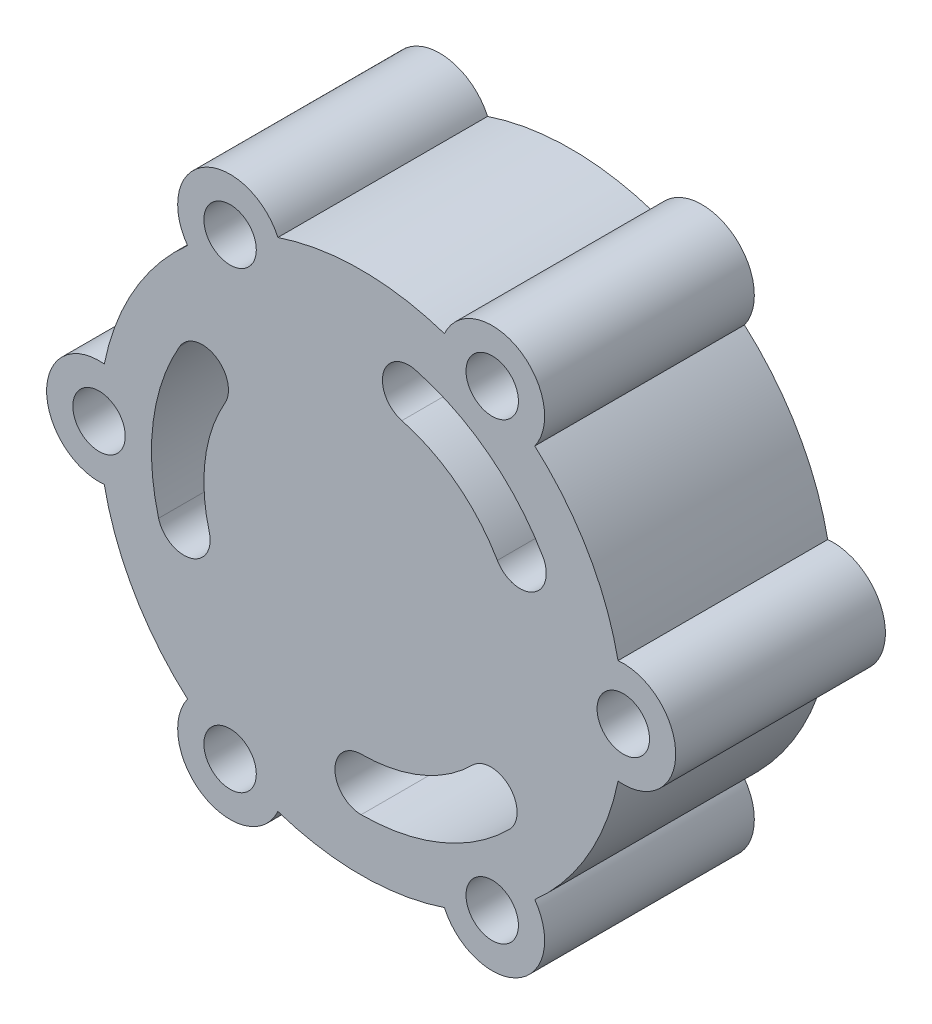
SolidWorks part; units mm, degrees
ref_plane "Front Plane" through (0, 0, 0) normal (0, 0, 1) x (1, 0, 0)
ref_plane "Top Plane" through (0, 0, 0) normal (0, 1, 0) x (1, 0, 0)
ref_plane "Right Plane" through (0, 0, 0) normal (1, 0, 0) x (0, 0, -1)
sketch "Sketch1" plane through (0, 0, 0) normal (0, 0, 1) x (1, 0, 0)
  line L0 (0, 0) -> (0, 50000) construction
  line L1 (0, 0) -> (-50000, 0) construction
  line L2 (70, 70) -> (105, 70) construction
  circle A0 centre (70, 70) radius 35 construction
  arc A1 (100.3109, 87.5) -> (79.0587, 103.8074) centre (70, 70) ccw construction
  arc A2 (104.641, 90) -> (80.3528, 108.637) centre (70, 70) ccw
  arc A3 (95.9808, 85) -> (77.7646, 98.9778) centre (70, 70) ccw
  arc A4 (95.9808, 85) -> (104.641, 90) centre (100.3109, 87.5) ccw
  arc A5 (80.3528, 108.637) -> (77.7646, 98.9778) centre (79.0587, 103.8074) ccw
  arc A6 (70, 35) -> (94.7487, 45.2513) centre (70, 70) ccw construction
  arc A7 (70, 30) -> (98.2843, 41.7157) centre (70, 70) ccw
  arc A8 (70, 40) -> (91.2132, 48.7868) centre (70, 70) ccw
  arc A9 (70, 40) -> (70, 30) centre (70, 35) ccw
  arc A10 (98.2843, 41.7157) -> (91.2132, 48.7868) centre (94.7487, 45.2513) ccw
  arc A11 (39.6891, 87.5) -> (36.1926, 60.9413) centre (70, 70) ccw construction
  arc A12 (35.359, 90) -> (31.363, 59.6472) centre (70, 70) ccw
  arc A13 (44.0192, 85) -> (41.0222, 62.2354) centre (70, 70) ccw
  arc A14 (44.0192, 85) -> (35.359, 90) centre (39.6891, 87.5) ccw
  arc A15 (31.363, 59.6472) -> (41.0222, 62.2354) centre (36.1926, 60.9413) ccw
  circle A17 centre (120, 70) radius 5
  arc A18 (119, 60.0501) -> (119, 79.9499) centre (120, 70) ccw
  arc A19 (85.8832, 22.5898) -> (103.1168, 32.5397) centre (95, 26.6987) ccw
  circle A20 centre (95, 26.6987) radius 5
  arc A21 (36.8832, 32.5397) -> (54.1168, 22.5898) centre (45, 26.6987) ccw
  circle A22 centre (45, 26.6987) radius 5
  arc A23 (21, 79.9499) -> (21, 60.0501) centre (20, 70) ccw
  circle A24 centre (20, 70) radius 5
  arc A25 (54.1168, 117.4102) -> (36.8832, 107.4603) centre (45, 113.3013) ccw
  circle A26 centre (45, 113.3013) radius 5
  arc A27 (103.1168, 107.4603) -> (85.8832, 117.4102) centre (95, 113.3013) ccw
  circle A28 centre (95, 113.3013) radius 5
  arc A29 (36.8832, 107.4603) -> (21, 79.9499) centre (70, 70) ccw
  arc A30 (85.8832, 117.4102) -> (54.1168, 117.4102) centre (70, 70) ccw
  arc A31 (21, 60.0501) -> (36.8832, 32.5397) centre (70, 70) ccw
  arc A32 (54.1168, 22.5898) -> (85.8832, 22.5898) centre (70, 70) ccw
  arc A33 (103.1168, 32.5397) -> (119, 60.0501) centre (70, 70) ccw
  arc A34 (119, 79.9499) -> (103.1168, 107.4603) centre (70, 70) ccw
  point P5 (91.3067, 97.7674)
  point P21 (83.3939, 37.6642)
  point P28 (35.2994, 74.5684)
  point P33 (70, 70)
  point P34 (0, 0)
  point P36 (0, 0)
  point P52 (70, 70)
  point P57 (0, 0)
  point P59 (0, 0)
  dimension "D1" = 70
  dimension "D3" = 70
  dimension "D4" = 10
  dimension "D6" = 35
  dimension "D9" = 50
  dimension "D10" = 10
  dimension "D11" = 20
  dimension "D2" = 70
  dimension "D7" = 30
  dimension "D8" = 3
  dimension "D5" = 45
  dimension "D12" = 6
extrude "Boss-Extrude1" add sketch "Sketch1" along normal blind 40
